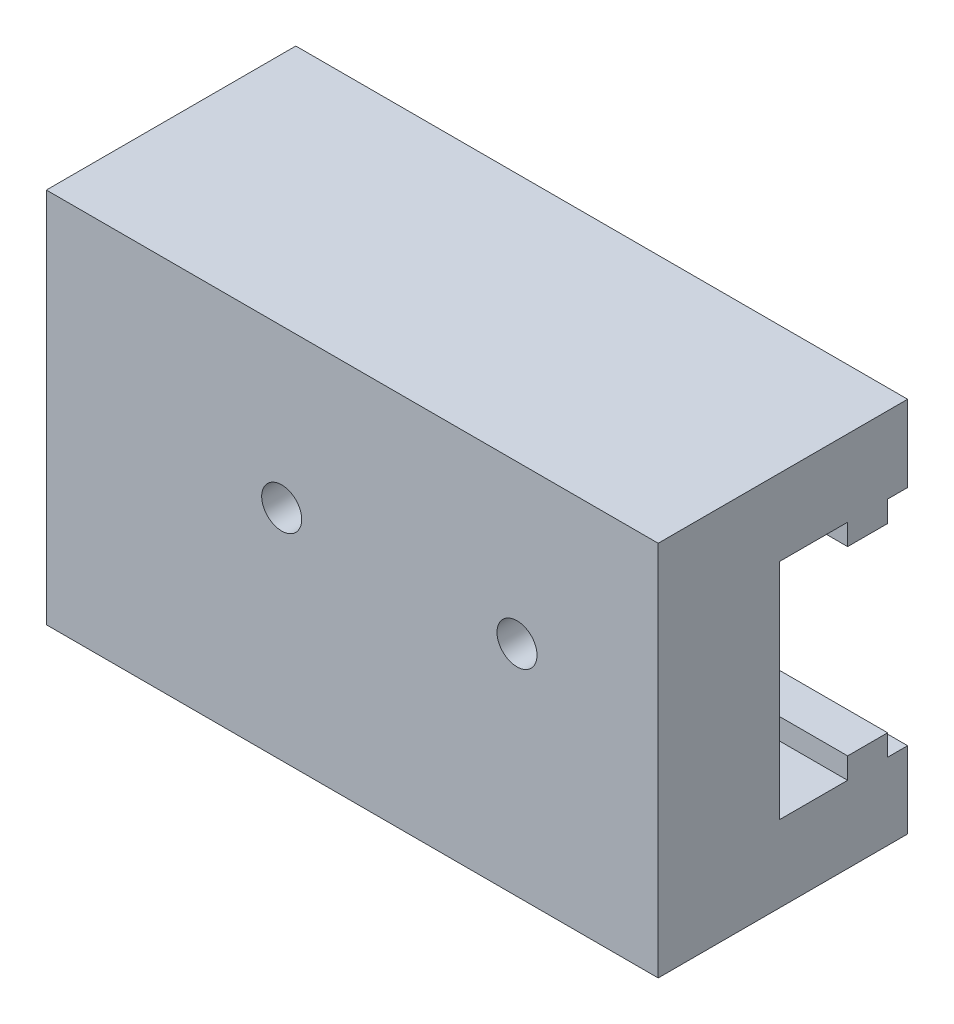
SolidWorks part; units mm, degrees
ref_plane "前视基准面" through (0, 0, 0) normal (0, 0, 1) x (1, 0, 0)
ref_plane "上视基准面" through (0, 0, 0) normal (0, 1, 0) x (1, 0, 0)
ref_plane "右视基准面" through (0, 0, 0) normal (1, 0, 0) x (0, 0, -1)
other "Configuration Table"
sketch "Carriage block profile" plane through (0, 0, 0) normal (0, 0, 1) x (1, 0, 0)
  line L0 (-5, 10.5) -> (21, 10.5)
  line L1 (21, 10.5) -> (21, 26.5)
  line L2 (21, 26.5) -> (-5, 26.5)
  line L3 (-5, 26.5) -> (-5, 10.5)
extrude "Carriage block" add sketch "Carriage block profile" along normal blind 10.6 from offset 29.8
sketch "Rail running clearance profile" plane through (0, 0, 0) normal (0, 0, 1) x (1, 0, 0)
  line L0 (-5.1, 13.75) -> (21.1, 13.75)
  line L1 (21.1, 13.75) -> (21.1, 23.25)
  line L2 (21.1, 23.25) -> (-5.1, 23.25)
  line L3 (-5.1, 23.25) -> (-5.1, 13.75)
extrude "Rail running clearance" cut sketch "Rail running clearance profile" along normal blind 5.55 from offset 29.7
sketch "Longitudinal guide keys profile" plane through (0, 0, 0) normal (0, 0, 1) x (1, 0, 0)
  line L0 (-5, 13.65) -> (21, 13.65)
  line L1 (21, 13.65) -> (21, 14.65)
  line L2 (21, 14.65) -> (-5, 14.65)
  line L3 (-5, 14.65) -> (-5, 13.65)
  line L4 (-5, 22.35) -> (21, 22.35)
  line L5 (21, 22.35) -> (21, 23.35)
  line L6 (21, 23.35) -> (-5, 23.35)
  line L7 (-5, 23.35) -> (-5, 22.35)
extrude "Longitudinal guide keys" add sketch "Longitudinal guide keys profile" along normal blind 1.7 from offset 30.65
sketch "Carriage screw pilots profile" plane through (0, 0, 0) normal (0, 0, 1) x (1, 0, 0)
  circle A0 centre (5, 19.8) radius 0.85
  circle A1 centre (15, 19.8) radius 0.85
extrude "Carriage screw pilots" cut sketch "Carriage screw pilots profile" along normal blind 3.6 from offset 36.9
